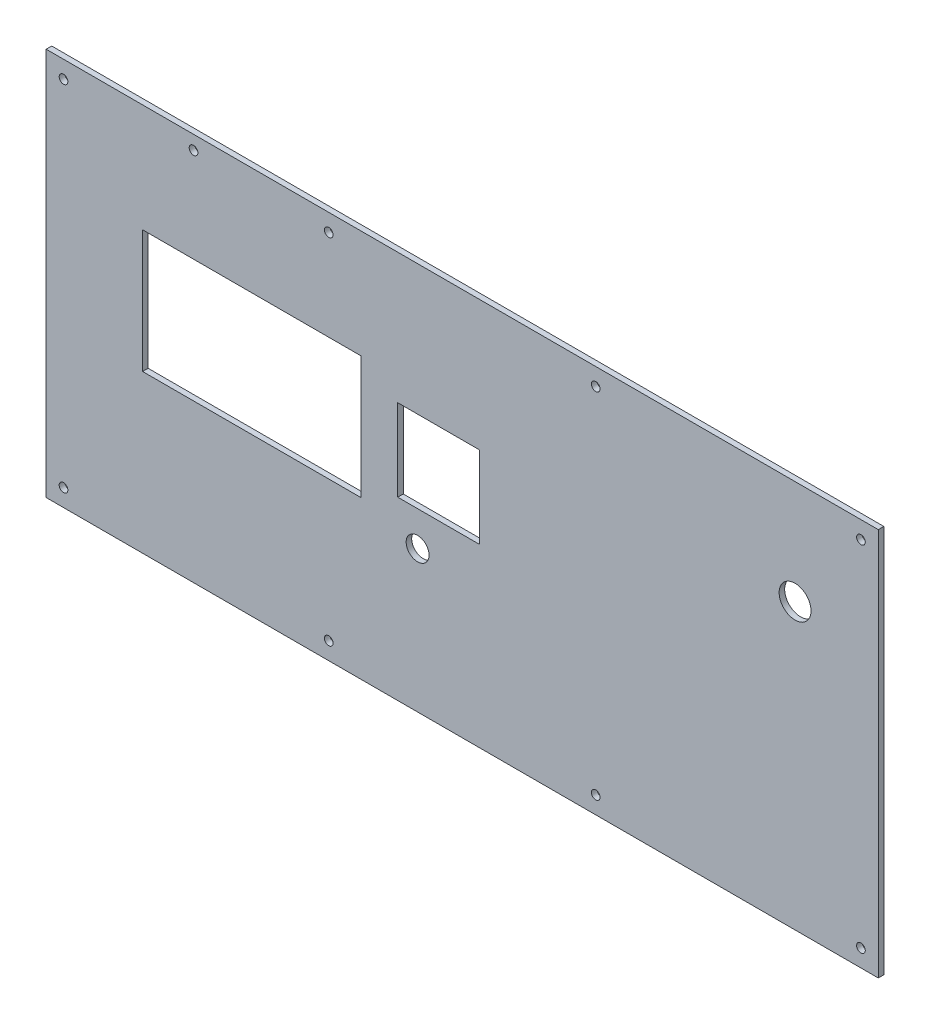
SolidWorks part; units mm, degrees
material "Acrylic (Medium-high impact)"
ref_plane "Front Plane" through (0, 0, 0) normal (0, 0, 1) x (1, 0, 0)
ref_plane "Top Plane" through (0, 0, 0) normal (0, 1, 0) x (1, 0, 0)
ref_plane "Right Plane" through (0, 0, 0) normal (1, 0, 0) x (0, 0, -1)
sketch "Sketch1" plane through (0, 0, 0) normal (0, 0, 1) x (1, 0, 0)
  line L1 (-97.155, 142.24) -> (207.645, 142.24)
  line L2 (-97.155, 142.24) -> (-97.155, 0)
  line L3 (-97.155, 0) -> (207.645, 0)
  line L4 (207.645, 142.24) -> (207.645, 0)
extrude "Extrude1" add sketch "Sketch1" along normal blind 2.032
sketch "Sketch3" plane through (0, 0, 2.032) normal (0, 0, 1) x (1, 0, 0)
  line L0 (-90.805, -9.4597) -> (-90.805, 127.5192) construction
  line L1 (-97.155, 129.794) -> (-84.455, 129.794) construction
  line L2 (55.245, 142.24) -> (55.245, 320.3404) construction
  line L3 (6.35, -13.5569) -> (6.35, 321.8506) construction
  line L4 (12.7, 142.24) -> (12.7, 215.9) construction
  line L5 (0, 142.24) -> (0, 215.9) construction
  line L6 (-71.755, 6.35) -> (-50.2069, 6.35) construction
  line L8 (-84.455, 0) -> (-84.455, 12.7) construction
  line L11 (-97.155, 135.89) -> (207.645, 135.89)
  line L12 (-97.155, 135.89) -> (182.245, 135.89) construction
  circle A0 centre (-90.805, 135.89) radius 1.5875
  circle A1 centre (-90.805, 6.35) radius 1.5875
  circle A2 centre (6.35, 135.89) radius 1.5875
  circle A3 centre (6.35, 6.35) radius 1.5875
  circle A4 centre (104.14, 6.35) radius 1.5875
  circle A5 centre (104.14, 135.89) radius 1.5875
  circle A6 centre (201.295, 6.35) radius 1.5875
  circle A7 centre (201.295, 135.89) radius 1.5875
  point P2 (-90.805, 129.794)
  point P18 (-84.455, 6.35)
  point P40 (201.295, 129.794)
  dimension "D2" = 3.175
  dimension "D1" = 6.35
extrude "Cut-Extrude1" cut sketch "Sketch3" against normal through all
sketch "Sketch4" plane through (0, 0, 2.032) normal (0, 0, 1) x (1, 0, 0)
  line L0 (207.645, 142.24) -> (-97.155, 142.24) construction
  line L1 (-84.455, 142.24) -> (0, 142.24) construction
  line L2 (-84.455, 142.24) -> (-84.455, 12.7) construction
  line L3 (-84.455, 12.7) -> (0, 12.7) construction
  line L4 (0, 142.24) -> (0, 12.7) construction
  line L5 (-97.155, 142.24) -> (-97.155, 0) construction
  line L6 (-97.155, 0) -> (207.645, 0) construction
  line L7 (-84.455, 139.7) -> (0, 139.7) construction
  line L8 (207.645, 0) -> (207.645, 142.24) construction
  line L10 (-61.849, 102.616) -> (18.161, 102.616)
  line L11 (-61.849, 102.616) -> (-61.849, 57.658)
  line L12 (-61.849, 57.658) -> (18.161, 57.658)
  line L13 (18.161, 102.616) -> (18.161, 57.658)
  line L14 (207.645, 142.24) -> (-97.155, 142.24) construction
  line L15 (31.623, 64.516) -> (61.595, 64.516)
  line L16 (31.623, 64.516) -> (31.623, 94.488)
  line L17 (31.623, 94.488) -> (61.595, 94.488)
  line L20 (-97.155, 142.24) -> (207.645, 142.24) construction
  line L23 (61.595, 64.516) -> (61.595, 94.488)
  circle A0 centre (6.35, 6.35) radius 1.5875 construction
  circle A1 centre (38.895, 51.84) radius 4.191
  circle A2 centre (38.895, 51.84) radius 4.25 construction
  circle A4 centre (-43.18, 137.16) radius 1.5875
  circle A8 centre (177.165, 104.14) radius 5.842
  dimension "D5" = 29.972
  dimension "D8" = 3.175
  dimension "D11" = 35.306
  dimension "D13" = 13.462
  dimension "D18" = 11.684
  dimension "D6" = 44.958
  dimension "D14" = 8.382
  dimension "D1" = 12.7
  dimension "D2" = 12.7
  dimension "D3" = 6.35
  dimension "D4" = 80.01
  dimension "D7" = 2.54
  dimension "D9" = 5.08
  dimension "D10" = 41.275
  dimension "D12" = 39.624
  dimension "D15" = 47.752
  dimension "D19" = 30.48
  dimension "D20" = 38.1
extrude "Extrude2" cut sketch "Sketch4" against normal through all
